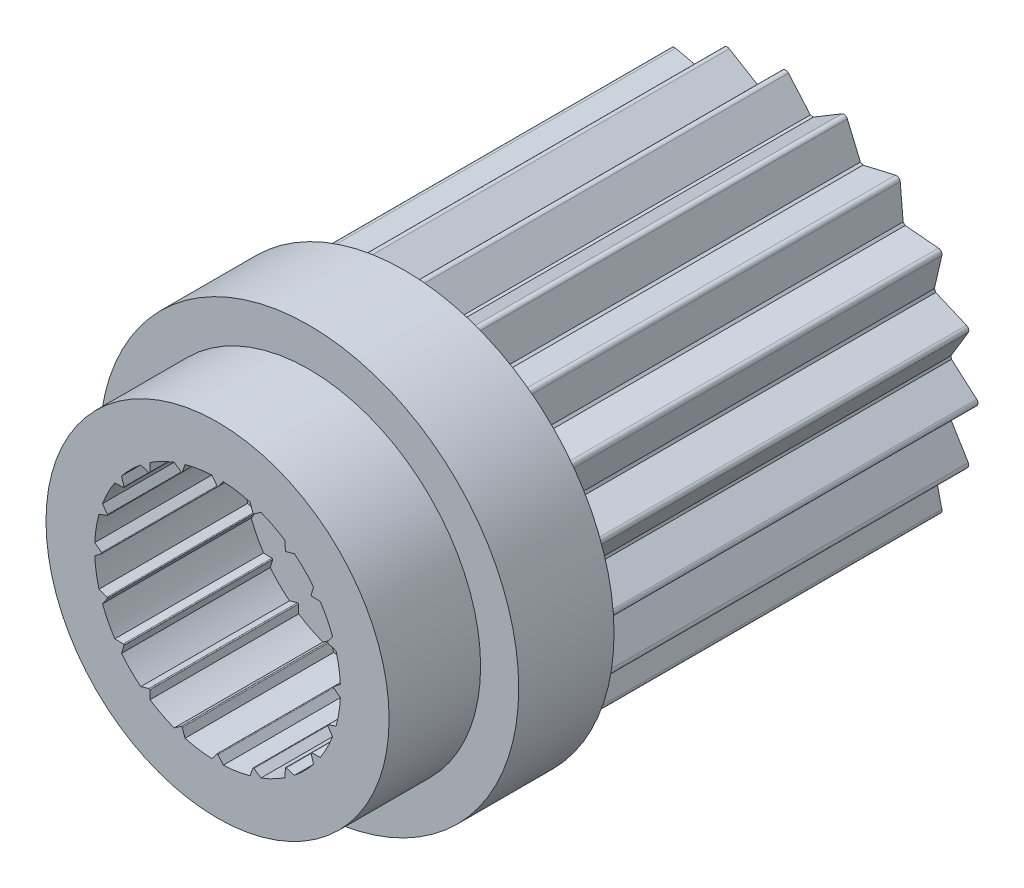
SolidWorks part; units mm, degrees
ref_plane "Front Plane" through (0, 0, 0) normal (0, 0, 1) x (1, 0, 0)
ref_plane "Top Plane" through (0, 0, 0) normal (0, 1, 0) x (1, 0, 0)
ref_plane "Right Plane" through (0, 0, 0) normal (1, 0, 0) x (0, 0, -1)
sketch "Sketch3" plane through (0, 0, 0) normal (1, 0, 0) x (0, 0, -1)
  line L0 (-3.844, 0) -> (6.2132, 0) construction
  line L1 (-3.9, 3.225) -> (-3.9, 4.5)
  line L2 (-3.9, 4.5) -> (-1.5, 4.5)
  line L3 (-1.5, 4.5) -> (-1.5, 5.5)
  line L4 (1, 4.4) -> (11, 4.4)
  line L5 (11, 4.4) -> (11, 1.75)
  line L6 (11, 1.75) -> (1.5, 1.75)
  line L8 (1.5, 1.75) -> (0, 1.75)
  line L9 (0, 1.75) -> (0, 3.225)
  line L10 (0, 3.225) -> (-3.9, 3.225)
  line L14 (-1.5, 5.5) -> (1, 5.5)
  line L15 (1, 4.4) -> (1, 5.5)
  dimension "D1" = 2.4
  dimension "D2" = 1.5
  dimension "D3" = 3.9
  dimension "D4" = 4.4
  dimension "D5" = 1.75
  dimension "D6" = 6.45
  dimension "D7" = 4.5
  dimension "D8" = 10
  dimension "D9" = 2.5
  dimension "D10" = 5.5
revolve "Revolve1" add sketch "Sketch3" angle 360 about L0
sketch "Sketch5" plane through (0, 0, -11) normal (0, 0, -1) x (-1, 0, 0)
  line L0 (-0.65, 4.3517) -> (-0.0755, 5.0131)
  line L1 (0.0755, 5.0131) -> (0.65, 4.3517)
  line L2 (0.7266, 4.3396) -> (1.4773, 4.7911)
  line L3 (1.6209, 4.7444) -> (1.9629, 3.9379)
  line L4 (2.032, 3.9027) -> (2.8855, 4.1001)
  line L5 (3.0077, 4.0113) -> (3.0837, 3.1386)
  line L6 (3.1386, 3.0837) -> (4.0113, 3.0077)
  line L7 (4.1001, 2.8855) -> (3.9027, 2.032)
  line L8 (3.9379, 1.9629) -> (4.7444, 1.6209)
  line L9 (4.7911, 1.4773) -> (4.3396, 0.7266)
  line L10 (4.3517, 0.65) -> (5.0131, 0.0755)
  line L11 (5.0131, -0.0755) -> (4.3517, -0.65)
  line L12 (4.3396, -0.7266) -> (4.7911, -1.4773)
  line L13 (4.7444, -1.6209) -> (3.9379, -1.9629)
  line L14 (3.9027, -2.032) -> (4.1001, -2.8855)
  line L15 (4.0113, -3.0077) -> (3.1386, -3.0837)
  line L16 (3.0837, -3.1386) -> (3.0077, -4.0113)
  line L17 (2.8855, -4.1001) -> (2.032, -3.9027)
  line L18 (1.9629, -3.9379) -> (1.6209, -4.7444)
  line L19 (1.4773, -4.7911) -> (0.7266, -4.3396)
  line L20 (0.65, -4.3517) -> (0.0755, -5.0131)
  line L21 (-0.0755, -5.0131) -> (-0.65, -4.3517)
  line L22 (-0.7266, -4.3396) -> (-1.4773, -4.7911)
  line L23 (-1.6209, -4.7444) -> (-1.9629, -3.9379)
  line L24 (-2.032, -3.9027) -> (-2.8855, -4.1001)
  line L25 (-3.0077, -4.0113) -> (-3.0837, -3.1386)
  line L26 (-3.1386, -3.0837) -> (-4.0113, -3.0077)
  line L27 (-4.1001, -2.8855) -> (-3.9027, -2.032)
  line L28 (-3.9379, -1.9629) -> (-4.7444, -1.6209)
  line L29 (-4.7911, -1.4773) -> (-4.3396, -0.7266)
  line L30 (-4.3517, -0.65) -> (-5.0131, -0.0755)
  line L31 (-5.0131, 0.0755) -> (-4.3517, 0.65)
  line L32 (-4.3396, 0.7266) -> (-4.7911, 1.4773)
  line L33 (-4.7444, 1.6209) -> (-3.9379, 1.9629)
  line L34 (-3.9027, 2.032) -> (-4.1001, 2.8855)
  line L35 (-4.0113, 3.0077) -> (-3.1386, 3.0837)
  line L36 (-3.0837, 3.1386) -> (-3.0077, 4.0113)
  line L37 (-2.8855, 4.1001) -> (-2.032, 3.9027)
  line L38 (-1.9629, 3.9379) -> (-1.6209, 4.7444)
  line L39 (-1.4773, 4.7911) -> (-0.7266, 4.3396)
  circle A0 centre (0, 0) radius 4.4 construction
  arc A1 (-0.0755, 5.0131) -> (0.0755, 5.0131) centre (0, 4.9475) cw
  arc A2 (1.4773, 4.7911) -> (1.6209, 4.7444) centre (1.5289, 4.7054) cw
  arc A3 (2.8855, 4.1001) -> (3.0077, 4.0113) centre (2.9081, 4.0026) cw
  arc A4 (4.0113, 3.0077) -> (4.1001, 2.8855) centre (4.0026, 2.9081) cw
  arc A5 (4.7444, 1.6209) -> (4.7911, 1.4773) centre (4.7054, 1.5289) cw
  arc A6 (5.0131, 0.0755) -> (5.0131, -0.0755) centre (4.9475, 0) cw
  arc A7 (4.7911, -1.4773) -> (4.7444, -1.6209) centre (4.7054, -1.5289) cw
  arc A8 (4.1001, -2.8855) -> (4.0113, -3.0077) centre (4.0026, -2.9081) cw
  arc A9 (3.0077, -4.0113) -> (2.8855, -4.1001) centre (2.9081, -4.0026) cw
  arc A10 (1.6209, -4.7444) -> (1.4773, -4.7911) centre (1.5289, -4.7054) cw
  arc A11 (0.0755, -5.0131) -> (-0.0755, -5.0131) centre (0, -4.9475) cw
  arc A12 (-1.4773, -4.7911) -> (-1.6209, -4.7444) centre (-1.5289, -4.7054) cw
  arc A13 (-2.8855, -4.1001) -> (-3.0077, -4.0113) centre (-2.9081, -4.0026) cw
  arc A14 (-4.0113, -3.0077) -> (-4.1001, -2.8855) centre (-4.0026, -2.9081) cw
  arc A15 (-4.7444, -1.6209) -> (-4.7911, -1.4773) centre (-4.7054, -1.5289) cw
  arc A16 (-5.0131, -0.0755) -> (-5.0131, 0.0755) centre (-4.9475, 0) cw
  arc A17 (-4.7911, 1.4773) -> (-4.7444, 1.6209) centre (-4.7054, 1.5289) cw
  arc A18 (-4.1001, 2.8855) -> (-4.0113, 3.0077) centre (-4.0026, 2.9081) cw
  arc A19 (-3.0077, 4.0113) -> (-2.8855, 4.1001) centre (-2.9081, 4.0026) cw
  arc A20 (-1.6209, 4.7444) -> (-1.4773, 4.7911) centre (-1.5289, 4.7054) cw
  arc A21 (-0.7266, 4.3396) -> (-1.9629, 3.9379) centre (0, 0) ccw
  arc A22 (0.65, 4.3517) -> (-0.65, 4.3517) centre (0, 0) ccw
  arc A23 (1.9629, 3.9379) -> (0.7266, 4.3396) centre (0, 0) ccw
  arc A24 (3.0837, 3.1386) -> (2.032, 3.9027) centre (0, 0) ccw
  arc A25 (3.9027, 2.032) -> (3.1386, 3.0837) centre (0, 0) ccw
  arc A26 (4.3396, 0.7266) -> (3.9379, 1.9629) centre (0, 0) ccw
  arc A27 (4.3517, -0.65) -> (4.3517, 0.65) centre (0, 0) ccw
  arc A28 (3.9379, -1.9629) -> (4.3396, -0.7266) centre (0, 0) ccw
  arc A29 (3.1386, -3.0837) -> (3.9027, -2.032) centre (0, 0) ccw
  arc A30 (2.032, -3.9027) -> (3.0837, -3.1386) centre (0, 0) ccw
  arc A31 (0.7266, -4.3396) -> (1.9629, -3.9379) centre (0, 0) ccw
  arc A32 (-0.65, -4.3517) -> (0.65, -4.3517) centre (0, 0) ccw
  arc A33 (-1.9629, -3.9379) -> (-0.7266, -4.3396) centre (0, 0) ccw
  arc A34 (-3.0837, -3.1386) -> (-2.032, -3.9027) centre (0, 0) ccw
  arc A35 (-3.9027, -2.032) -> (-3.1386, -3.0837) centre (0, 0) ccw
  arc A36 (-4.3396, -0.7266) -> (-3.9379, -1.9629) centre (0, 0) ccw
  arc A37 (-4.3517, 0.65) -> (-4.3517, -0.65) centre (0, 0) ccw
  arc A38 (-3.9379, 1.9629) -> (-4.3396, 0.7266) centre (0, 0) ccw
  arc A39 (-3.1386, 3.0837) -> (-3.9027, 2.032) centre (0, 0) ccw
  arc A40 (-2.032, 3.9027) -> (-3.0837, 3.1386) centre (0, 0) ccw
  point P8 (0, 4.4)
  point P19 (0, 5.1)
  point P106 (0, 0)
  dimension "D4" = 0.1
  dimension "D1" = 0.7
  dimension "D2" = 0.65
  dimension "D3" = 0.65
  dimension "D5" = 20
extrude "Boss-Extrude3" add sketch "Sketch5" against normal up to next
sketch "Sketch6" plane through (0, 0, 3.9) normal (0, 0, 1) x (1, 0, 0)
  line L0 (-0.15, 3.2215) -> (-0.0159, 3.0458)
  line L1 (0.0159, 3.0458) -> (0.15, 3.2215)
  line L2 (0, 0) -> (0, 3.225) construction
  line L3 (0.9563, 2.8918) -> (1.1382, 3.0175)
  line L4 (0.8528, 3.1102) -> (0.9261, 2.9017)
  line L5 (1.8032, 2.4548) -> (2.0149, 2.5181)
  line L6 (1.7722, 2.6944) -> (1.7774, 2.4735)
  line L7 (2.4735, 1.7774) -> (2.6944, 1.7722)
  line L8 (2.5181, 2.0149) -> (2.4548, 1.8032)
  line L9 (2.9017, 0.9261) -> (3.1102, 0.8528)
  line L10 (3.0175, 1.1382) -> (2.8918, 0.9563)
  line L11 (3.0458, -0.0159) -> (3.2215, -0.15)
  line L12 (3.2215, 0.15) -> (3.0458, 0.0159)
  line L13 (2.8918, -0.9563) -> (3.0175, -1.1382)
  line L14 (3.1102, -0.8528) -> (2.9017, -0.9261)
  line L15 (2.4548, -1.8032) -> (2.5181, -2.0149)
  line L16 (2.6944, -1.7722) -> (2.4735, -1.7774)
  line L17 (1.7774, -2.4735) -> (1.7722, -2.6944)
  line L18 (2.0149, -2.5181) -> (1.8032, -2.4548)
  line L19 (0.9261, -2.9017) -> (0.8528, -3.1102)
  line L20 (1.1382, -3.0175) -> (0.9563, -2.8918)
  line L21 (-0.0159, -3.0458) -> (-0.15, -3.2215)
  line L22 (0.15, -3.2215) -> (0.0159, -3.0458)
  line L23 (-0.9563, -2.8918) -> (-1.1382, -3.0175)
  line L24 (-0.8528, -3.1102) -> (-0.9261, -2.9017)
  line L25 (-1.8032, -2.4548) -> (-2.0149, -2.5181)
  line L26 (-1.7722, -2.6944) -> (-1.7774, -2.4735)
  line L27 (-2.4735, -1.7774) -> (-2.6944, -1.7722)
  line L28 (-2.5181, -2.0149) -> (-2.4548, -1.8032)
  line L29 (-2.9017, -0.9261) -> (-3.1102, -0.8528)
  line L30 (-3.0175, -1.1382) -> (-2.8918, -0.9563)
  line L31 (-3.0458, 0.0159) -> (-3.2215, 0.15)
  line L32 (-3.2215, -0.15) -> (-3.0458, -0.0159)
  line L33 (-2.8918, 0.9563) -> (-3.0175, 1.1382)
  line L34 (-3.1102, 0.8528) -> (-2.9017, 0.9261)
  line L35 (-2.4548, 1.8032) -> (-2.5181, 2.0149)
  line L36 (-2.6944, 1.7722) -> (-2.4735, 1.7774)
  line L37 (-1.7774, 2.4735) -> (-1.7722, 2.6944)
  line L38 (-2.0149, 2.5181) -> (-1.8032, 2.4548)
  line L39 (-0.9261, 2.9017) -> (-0.8528, 3.1102)
  line L40 (-1.1382, 3.0175) -> (-0.9563, 2.8918)
  circle A0 centre (0, 0) radius 3.225 construction
  circle A1 centre (0, 0) radius 3.225 construction
  arc A2 (-1.7722, 2.6944) -> (-2.0149, 2.5181) centre (0, 0) ccw
  arc A3 (-0.0159, 3.0458) -> (0.0159, 3.0458) centre (0, 3.058) ccw
  arc A4 (0.9261, 2.9017) -> (0.9563, 2.8918) centre (0.945, 2.9083) ccw
  arc A5 (1.7774, 2.4735) -> (1.8032, 2.4548) centre (1.7974, 2.4739) ccw
  arc A6 (2.4548, 1.8032) -> (2.4735, 1.7774) centre (2.4739, 1.7974) ccw
  arc A7 (2.8918, 0.9563) -> (2.9017, 0.9261) centre (2.9083, 0.945) ccw
  arc A8 (3.0458, 0.0159) -> (3.0458, -0.0159) centre (3.058, 0) ccw
  arc A9 (2.9017, -0.9261) -> (2.8918, -0.9563) centre (2.9083, -0.945) ccw
  arc A10 (2.4735, -1.7774) -> (2.4548, -1.8032) centre (2.4739, -1.7974) ccw
  arc A11 (1.8032, -2.4548) -> (1.7774, -2.4735) centre (1.7974, -2.4739) ccw
  arc A12 (0.9563, -2.8918) -> (0.9261, -2.9017) centre (0.945, -2.9083) ccw
  arc A13 (0.0159, -3.0458) -> (-0.0159, -3.0458) centre (0, -3.058) ccw
  arc A14 (-0.9261, -2.9017) -> (-0.9563, -2.8918) centre (-0.945, -2.9083) ccw
  arc A15 (-1.7774, -2.4735) -> (-1.8032, -2.4548) centre (-1.7974, -2.4739) ccw
  arc A16 (-2.4548, -1.8032) -> (-2.4735, -1.7774) centre (-2.4739, -1.7974) ccw
  arc A17 (-2.8918, -0.9563) -> (-2.9017, -0.9261) centre (-2.9083, -0.945) ccw
  arc A18 (-3.0458, -0.0159) -> (-3.0458, 0.0159) centre (-3.058, 0) ccw
  arc A19 (-2.9017, 0.9261) -> (-2.8918, 0.9563) centre (-2.9083, 0.945) ccw
  arc A20 (-2.4735, 1.7774) -> (-2.4548, 1.8032) centre (-2.4739, 1.7974) ccw
  arc A21 (-1.8032, 2.4548) -> (-1.7774, 2.4735) centre (-1.7974, 2.4739) ccw
  arc A22 (-0.9563, 2.8918) -> (-0.9261, 2.9017) centre (-0.945, 2.9083) ccw
  arc A23 (-0.8528, 3.1102) -> (-1.1382, 3.0175) centre (0, 0) ccw
  arc A24 (0.15, 3.2215) -> (-0.15, 3.2215) centre (0, 0) ccw
  arc A25 (1.1382, 3.0175) -> (0.8528, 3.1102) centre (0, 0) ccw
  arc A26 (2.0149, 2.5181) -> (1.7722, 2.6944) centre (0, 0) ccw
  arc A27 (2.6944, 1.7722) -> (2.5181, 2.0149) centre (0, 0) ccw
  arc A28 (3.1102, 0.8528) -> (3.0175, 1.1382) centre (0, 0) ccw
  arc A29 (3.2215, -0.15) -> (3.2215, 0.15) centre (0, 0) ccw
  arc A30 (3.0175, -1.1382) -> (3.1102, -0.8528) centre (0, 0) ccw
  arc A31 (2.5181, -2.0149) -> (2.6944, -1.7722) centre (0, 0) ccw
  arc A32 (1.7722, -2.6944) -> (2.0149, -2.5181) centre (0, 0) ccw
  arc A33 (0.8528, -3.1102) -> (1.1382, -3.0175) centre (0, 0) ccw
  arc A34 (-0.15, -3.2215) -> (0.15, -3.2215) centre (0, 0) ccw
  arc A35 (-1.1382, -3.0175) -> (-0.8528, -3.1102) centre (0, 0) ccw
  arc A36 (-2.0149, -2.5181) -> (-1.7722, -2.6944) centre (0, 0) ccw
  arc A37 (-2.6944, -1.7722) -> (-2.5181, -2.0149) centre (0, 0) ccw
  arc A38 (-3.1102, -0.8528) -> (-3.0175, -1.1382) centre (0, 0) ccw
  arc A39 (-3.2215, 0.15) -> (-3.2215, -0.15) centre (0, 0) ccw
  arc A40 (-3.0175, 1.1382) -> (-3.1102, 0.8528) centre (0, 0) ccw
  arc A41 (-2.5181, 2.0149) -> (-2.6944, 1.7722) centre (0, 0) ccw
  point P14 (0, 3.025)
  point P110 (0, 0)
  dimension "D4" = 0.02
  dimension "D1" = 0.2
  dimension "D2" = 0.15
  dimension "D3" = 0.15
  dimension "D5" = 20
extrude "Boss-Extrude4" add sketch "Sketch6" against normal up to surface (3.9 mm away) up to face at (1.75, 0, 0)
sketch "Sketch7" plane through (0, 0, 0) normal (0, 0, 1) x (1, 0, 0)
  line L0 (-1, 3.066) -> (-1, 0)
  line L1 (-1, 0) -> (1, 0)
  line L2 (1, 0) -> (1, 3.066)
  arc A0 (1, 3.066) -> (-1, 3.066) centre (0, 0) ccw
  point P7 (0, 0)
  dimension "D1" = 6.45
  dimension "D2" = 2
extrude "Cut-Extrude1" cut sketch "Sketch7" against normal blind 2.2
